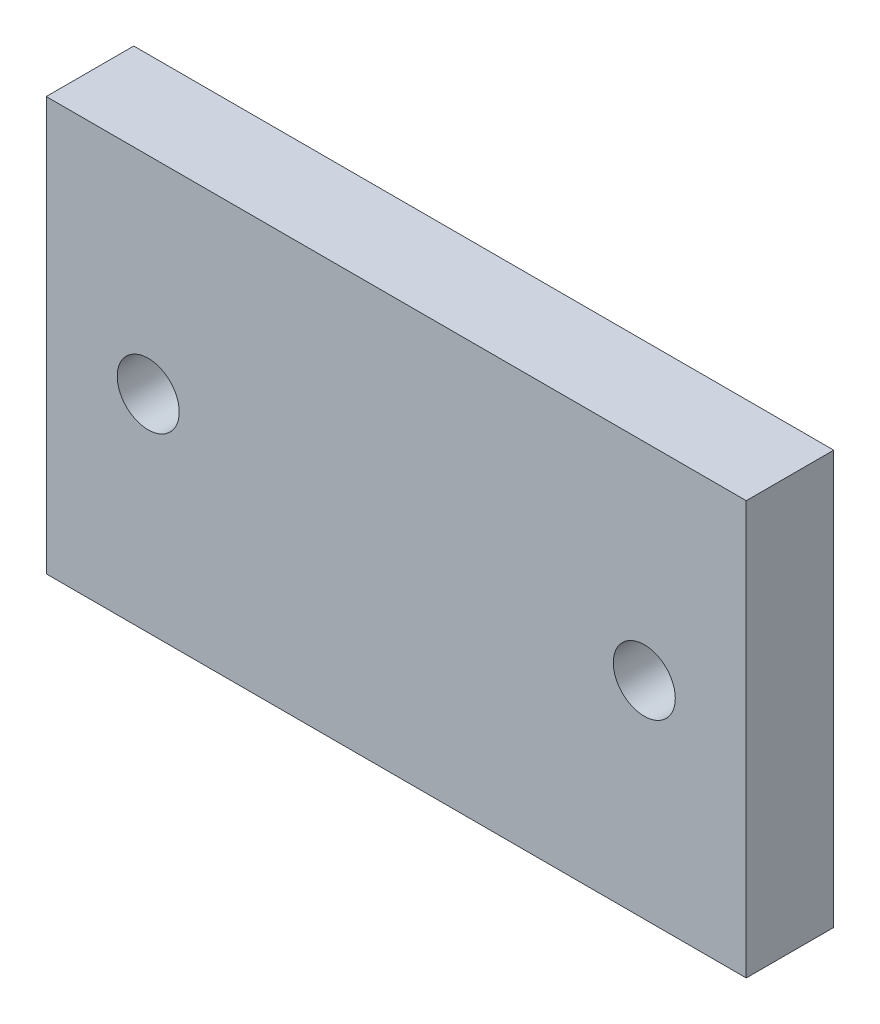
SolidWorks part; units mm, degrees
ref_plane "Front Plane" through (0, 0, 0) normal (0, 0, 1) x (1, 0, 0)
ref_plane "Top Plane" through (0, 0, 0) normal (0, 1, 0) x (1, 0, 0)
ref_plane "Right Plane" through (0, 0, 0) normal (1, 0, 0) x (0, 0, -1)
sketch "Sketch1" plane through (0, 0, 0) normal (0, 0, 1) x (1, 0, 0)
  line L0 (0, 15) -> (50.8, 15) construction
  line L1 (0, 0) -> (50.8, 0)
  line L2 (0, 0) -> (0, 30)
  line L3 (0, 30) -> (50.8, 30)
  line L4 (50.8, 0) -> (50.8, 30)
  circle A0 centre (7.4, 15) radius 2.25
  circle A1 centre (43.4, 15) radius 2.25
  dimension "D1" = 4.5
  dimension "D2" = 36
  dimension "D3" = 50.8
  dimension "D4" = 7.4
extrude "Boss-Extrude1" add sketch "Sketch1" along normal blind 6.35
sketch "Sketch2" plane through (0, 0, 0) normal (0, -1, 0) x (-1, 0, 0)
  line L0 (0, -3.175) -> (-50.8, -3.175) construction
  line L1 (0, -6.35) -> (0, 0) construction
  line L2 (-50.8, -6.35) -> (-50.8, 0) construction
  point P6 (-12.7, -3.175)
  point P7 (-38.1, -3.175)
  dimension "D1" = 25.4
  dimension "D2" = 12.7
hole_wizard "M4x0.7 Tapped Hole1" positions "Sketch4" profile "Sketch3" tap size "M4x0.7" standard "ANSI Metric"
sketch "Sketch4" plane through (0, 0, 0) normal (0, -1, 0) x (-1, 0, 0)
  point P0 (-12.7, -3.175)
  point P3 (-38.1, -3.175)
sketch "Sketch3" plane through (12.7, 0, 3.175) normal (1, 0, 0) x (0, 0, -1)
  line L0 (0, 0) -> (0, 15.7234)
  line L1 (0, 15.7234) -> (1.65, 14.732)
  line L2 (1.65, 14.732) -> (1.65, 0)
  line L5 (1.65, 0) -> (0, 0)
  line L10 (0, 15.7234) -> (-1.65, 14.732) construction
  line L11 (0, -6.35) -> (0, 107.95) construction
  dimension "Tap Drill Dia." = 3.3
  dimension "Tap Drill Depth" = 14.732
  dimension "Drill Angle" = 118
cosmetic thread "Hole Thread1" parameters "D1"=12.7, "D2"=4
cosmetic thread "Hole Thread2" parameters "D1"=12.7, "D2"=4
